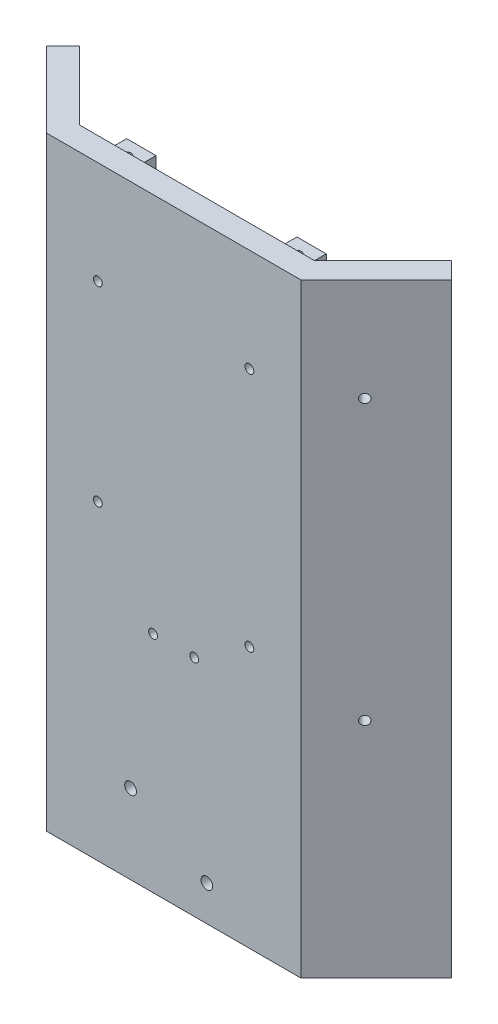
SolidWorks part; units mm, degrees
ref_plane "Front" through (0, 0, 0) normal (0, 0, 1) x (1, 0, 0)
ref_plane "Top" through (0, 0, 0) normal (0, 1, 0) x (1, 0, 0)
ref_plane "Right" through (0, 0, 0) normal (1, 0, 0) x (0, 0, -1)
sketch "Sketch1" plane through (0, 0, 0) normal (0, 1, 0) x (1, 0, 0)
  line L0 (-40, 0) -> (40, 0)
  line L1 (40, 0) -> (63.3345, 23.3345)
  line L2 (-40, 0) -> (-63.3345, 23.3345)
  line L3 (-43.3137, -8) -> (-68.9914, 17.6777)
  line L4 (-43.3137, -8) -> (43.3137, -8)
  line L5 (43.3137, -8) -> (68.9914, 17.6777)
  line L6 (-68.9914, 17.6777) -> (-63.3345, 23.3345)
  line L7 (68.9914, 17.6777) -> (63.3345, 23.3345)
  dimension "D1" = 80
  dimension "D2" = 33
  dimension "D3" = 33
  dimension "D4" = 135
  dimension "D5" = 135
  dimension "D6" = 8
extrude "Boss-Extrude1" add sketch "Sketch1" along normal blind 206
sketch "Sketch2" plane through (0, 0, 0) normal (0, 0, -1) x (-1, 0, 0)
  line L0 (-40, 206) -> (40, 206) construction
  line L1 (-34, 200) -> (-24, 200)
  line L2 (-34, 200) -> (-34, 194)
  line L3 (-34, 194) -> (-24, 194)
  line L4 (-24, 200) -> (-24, 194)
  line L5 (-34, 200) -> (-24, 194) construction
  line L6 (-34, 194) -> (-24, 200) construction
  line L7 (-40, 206) -> (-40, 0) construction
  line L8 (40, 206) -> (40, 0) construction
  line L9 (24, 200) -> (34, 200)
  line L10 (24, 200) -> (24, 194)
  line L11 (24, 194) -> (34, 194)
  line L12 (34, 200) -> (34, 194)
  line L13 (24, 200) -> (34, 194) construction
  line L14 (24, 194) -> (34, 200) construction
  point P0 (-29, 197)
  point P9 (29, 197)
  dimension "D1" = 6
  dimension "D2" = 10
  dimension "D3" = 6
  dimension "D4" = 6
  dimension "D5" = 6
  dimension "D6" = 10
  dimension "D7" = 6
  dimension "D8" = 6
extrude "Boss-Extrude2" add sketch "Sketch2" along normal blind 10
sketch "Sketch3" plane through (0, 200, 0) normal (0, 1, 0) x (1, 0, 0)
  line L0 (-34, 0) -> (-24, 10) construction
  line L1 (24, 0) -> (34, 10) construction
  circle A0 centre (-29, 5) radius 1.5
  circle A1 centre (29, 5) radius 1.5
  dimension "D1" = 3
  dimension "D2" = 3
extrude "Cut-Extrude1" cut sketch "Sketch3" against normal up to next
sketch "Sketch4" plane through (0, 0, 8) normal (0, 0, 1) x (1, 0, 0)
  line L0 (11.3137, 12) -> (-14.6671, 27) construction
  line L1 (-43.3137, 0) -> (43.3137, 0) construction
  line L2 (43.3137, 206) -> (43.3137, 0) construction
  circle A0 centre (-14.6671, 27) radius 2
  circle A1 centre (11.3137, 12) radius 2
  dimension "D2" = 4
  dimension "D3" = 4
  dimension "D1" = 30
  dimension "D4" = 12
  dimension "D5" = 30
  dimension "D6" = 32
extrude "Cut-Extrude2" cut sketch "Sketch4" against normal up to next
sketch "Sketch5" plane through (0, 0, 8) normal (0, 0, 1) x (1, 0, 0)
  line L0 (0, 0) -> (0, 76.4041) construction
  line L1 (-43.3137, 0) -> (43.3137, 0) construction
  line L2 (11.3137, 12) -> (42.9339, 66.7678) construction
  line L3 (0, 76.4041) -> (36.3731, 55.4041) construction
  line L4 (-7, 76.4041) -> (7, 76.4041) construction
  circle A0 centre (0, 76.4041) radius 2 construction
  circle A2 centre (-7, 76.4041) radius 1.5
  circle A3 centre (7, 76.4041) radius 1.5
  dimension "D2" = 4
  dimension "D4" = 50.1187
  dimension "D6" = 3
  dimension "D7" = 3
  dimension "D1" = 42
  dimension "D3" = 30
  dimension "D5" = 14
extrude "Cut-Extrude3" cut sketch "Sketch5" against normal up to next
sketch "Sketch6" plane through (0, 0, 8) normal (0, 0, 1) x (1, 0, 0)
  line L0 (-43.3137, 206) -> (43.3137, 206) construction
  line L1 (-43.3137, 206) -> (-43.3137, 0) construction
  line L2 (43.3137, 206) -> (43.3137, 0) construction
  circle A0 centre (-25.8137, 171) radius 1.5
  circle A1 centre (25.8137, 171) radius 1.5
  circle A2 centre (-25.8137, 106) radius 1.5
  circle A3 centre (25.8137, 89) radius 1.5
  dimension "D1" = 3
  dimension "D2" = 3
  dimension "D3" = 3
  dimension "D4" = 3
  dimension "D5" = 35
  dimension "D6" = 65
  dimension "D7" = 17.5
  dimension "D8" = 82
  dimension "D9" = 17.5
extrude "Cut-Extrude4" cut sketch "Sketch6" against normal up to next
sketch "Sketch7" plane through (-25.6569, 0, 25.6569) normal (-0.7071, 0, 0.7071) x (0.7071, 0, 0.7071)
  line L0 (-61.2843, 206) -> (-24.9706, 206) construction
  line L1 (-61.2843, 206) -> (-61.2843, 0) construction
  circle A0 centre (-43.4143, 171) radius 1.5
  circle A1 centre (-43.4143, 81) radius 1.5
  point P4 (0, 0)
  dimension "D1" = 3
  dimension "D2" = 3
  dimension "D3" = 35
  dimension "D4" = 90
  dimension "D5" = 17.87
extrude "Cut-Extrude5" cut sketch "Sketch7" against normal up to next
sketch "Sketch8" plane through (25.6569, 0, 25.6569) normal (0.7071, 0, 0.7071) x (0.7071, 0, -0.7071)
  line L0 (24.9706, 206) -> (61.2843, 206) construction
  line L1 (61.2843, 206) -> (61.2843, 0) construction
  circle A0 centre (40.3843, 171) radius 1.5
  circle A1 centre (40.3843, 76) radius 1.5
  point P4 (0, 0)
  dimension "D1" = 3
  dimension "D2" = 3
  dimension "D3" = 35
  dimension "D4" = 95
  dimension "D5" = 20.9
extrude "Cut-Extrude6" cut sketch "Sketch8" against normal up to next
